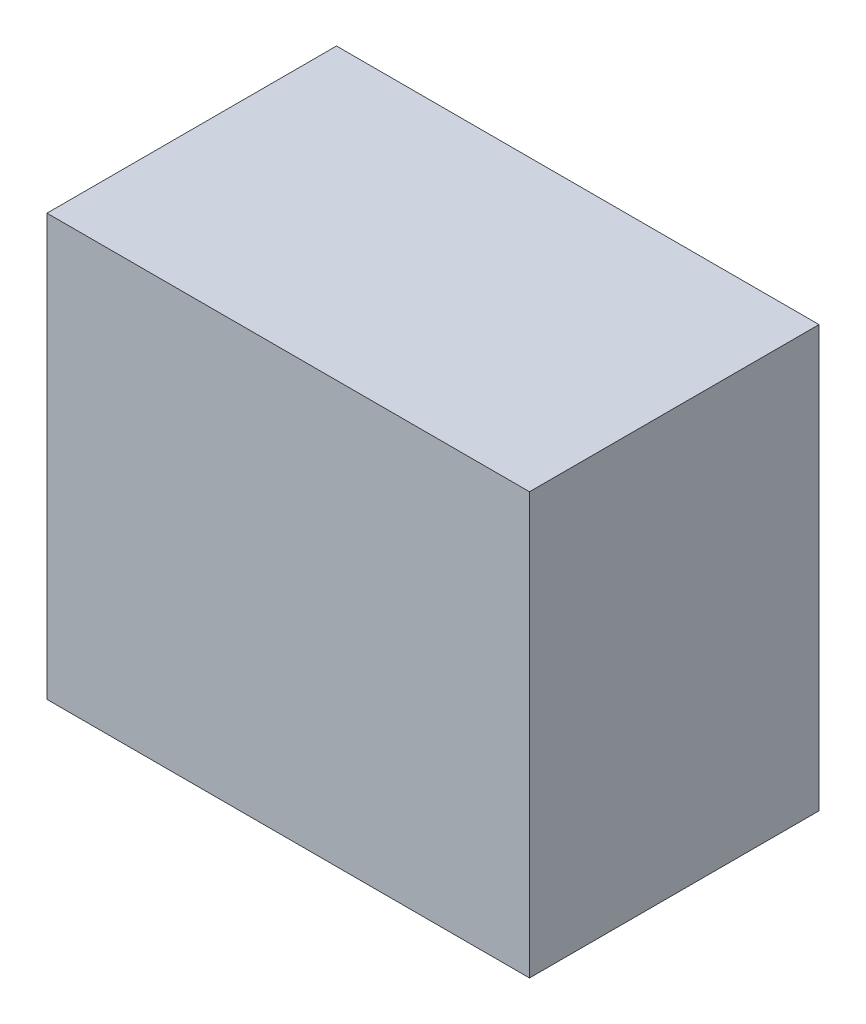
SolidWorks part; units mm, degrees
ref_plane "Front Plane" through (0, 0, 0) normal (0, 0, 1) x (1, 0, 0)
ref_plane "Top Plane" through (0, 0, 0) normal (0, 1, 0) x (1, 0, 0)
ref_plane "Right Plane" through (0, 0, 0) normal (1, 0, 0) x (0, 0, -1)
sketch "Sketch1" plane through (0, 0, 0) normal (0, 1, 0) x (1, 0, 0)
  line L1 (-27.5, 16.5) -> (27.5, 16.5)
  line L2 (-27.5, 16.5) -> (-27.5, -16.5)
  line L3 (-27.5, -16.5) -> (27.5, -16.5)
  line L4 (27.5, 16.5) -> (27.5, -16.5)
  line L5 (-27.5, 16.5) -> (27.5, -16.5) construction
  line L6 (-27.5, -16.5) -> (27.5, 16.5) construction
  point P0 (0, 0)
  dimension "D1" = 55
  dimension "D2" = 33
extrude "Boss-Extrude1" add sketch "Sketch1" along normal blind 48
ref_plane "Plane1" through (-25.75, 0, 0) normal (-1, 0, 0) x (0, 0, 1)
sketch "Sketch2" plane through (-25.75, 0, 0) normal (-1, 0, 0) x (0, 0, 1)
  line L0 (-16.5, 48) -> (16.5, 0) construction
  line L1 (16.5, 0) -> (16.5, 48) construction
  line L2 (16.5, 48) -> (-16.5, 0) construction
  line L3 (0, 0) -> (0, 48) construction
  line L4 (-16.5, 48) -> (16.5, 48) construction
  line L5 (0, 32) -> (0, 16) construction
  line L6 (14.7557, 32) -> (14.7557, 16)
  line L7 (-14.7556, 32) -> (-14.7557, 16)
  arc A0 (14.7557, 32) -> (-14.7556, 32) centre (0, 32) ccw
  arc A1 (-14.7557, 16) -> (14.7557, 16) centre (0, 16) ccw
  point P15 (0, 24)
  dimension "D1" = 29.5113
  dimension "D2" = 16
extrude "Cut-Extrude1" cut sketch "Sketch2" against normal blind 51.5
